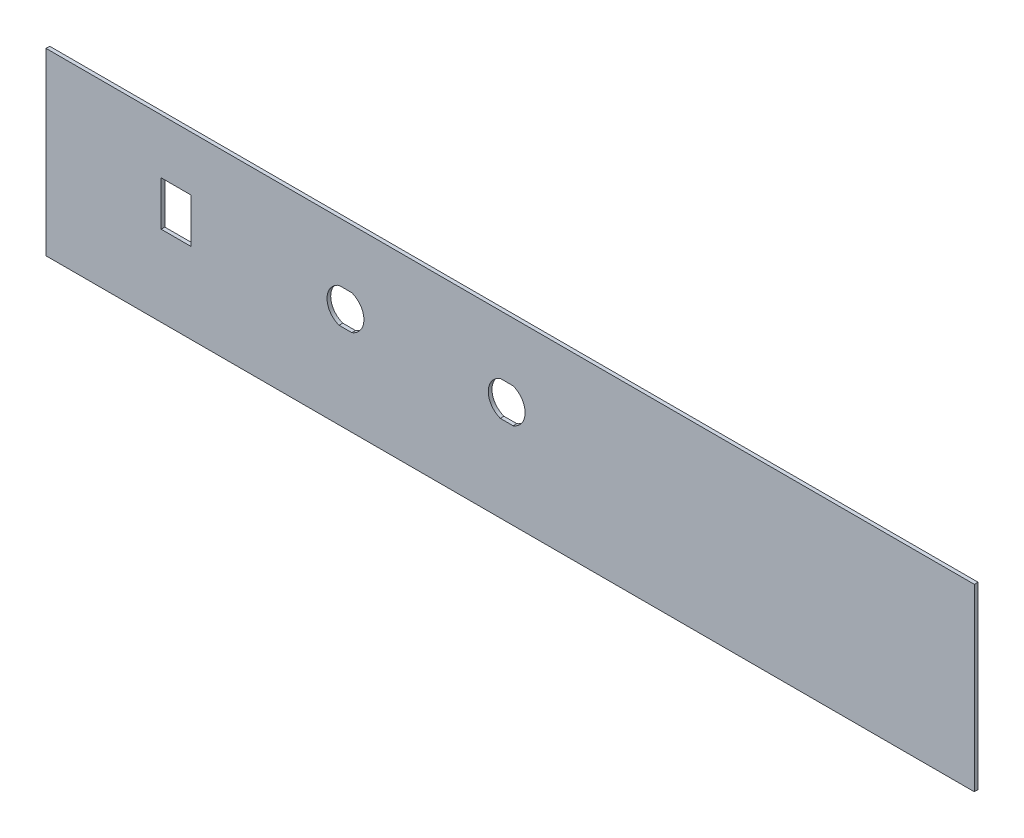
SolidWorks part; units mm, degrees
ref_plane "Front Plane" through (0, 0, 0) normal (0, 0, 1) x (1, 0, 0)
ref_plane "Top Plane" through (0, 0, 0) normal (0, 1, 0) x (1, 0, 0)
ref_plane "Right Plane" through (0, 0, 0) normal (1, 0, 0) x (0, 0, -1)
sketch "Panel" plane through (0, 0, 0) normal (0, 0, 1) x (1, 0, 0)
  line L1 (0, 0) -> (403, 0)
  line L2 (0, 0) -> (0, 78)
  line L3 (0, 78) -> (403, 78)
  line L4 (403, 0) -> (403, 78)
  dimension "D1" = 403
  dimension "D2" = 78
extrude "Boss-Extrude1" add sketch "Panel" along normal blind 1.6
sketch "Rocker_Switch" plane through (0, 0, 1.6) normal (0, 0, 1) x (1, 0, 0)
  line L1 (50, 54.33) -> (62.9, 54.33)
  line L2 (50, 54.33) -> (50, 35)
  line L3 (50, 35) -> (62.9, 35)
  line L4 (62.9, 54.33) -> (62.9, 35)
  dimension "D1" = 12.9
  dimension "D2" = 19.33
  dimension "D3" = 50
  dimension "D4" = 35
sketch "En/Disable" plane through (0, 0, 1.6) normal (0, 0, 1) x (1, 0, 0)
  line L0 (127.2163, 52.5001) -> (132.7837, 52.5001)
  line L1 (0, 0) -> (403, 0) construction
  line L2 (132.7837, 37.4999) -> (127.2163, 37.4999)
  arc A0 (127.2163, 52.5001) -> (127.2163, 37.4999) centre (130, 45) ccw
  arc A1 (132.7837, 37.4999) -> (132.7837, 52.5001) centre (130, 45) ccw
  dimension "D1" = 16
  dimension "D2" = 15.0001
  dimension "D4" = 130
  dimension "D5" = 45
sketch "Turbo" plane through (0, 0, 0) normal (0, 0, 1) x (1, 0, 0)
  line L0 (197.2163, 52.5001) -> (202.7837, 52.5001)
  line L1 (0, 0) -> (403, 0) construction
  line L2 (202.7837, 37.4999) -> (197.2163, 37.4999)
  arc A0 (197.2163, 52.5001) -> (197.2163, 37.4999) centre (200, 45) ccw
  arc A1 (202.7837, 37.4999) -> (202.7837, 52.5001) centre (200, 45) ccw
  point P1 (0, 0)
  point P4 (0, 0)
  point P6 (0, 0)
  dimension "D1" = 16
  dimension "D2" = 15.0001
  dimension "D3" = 200
  dimension "D4" = 45
extrude "Cut-Extrude2" cut sketch "Rocker_Switch" against normal blind 10
extrude "Cut-Extrude4" cut sketch "Turbo" along normal blind 10
extrude "Cut-Extrude6" cut sketch "En/Disable" against normal blind 10
